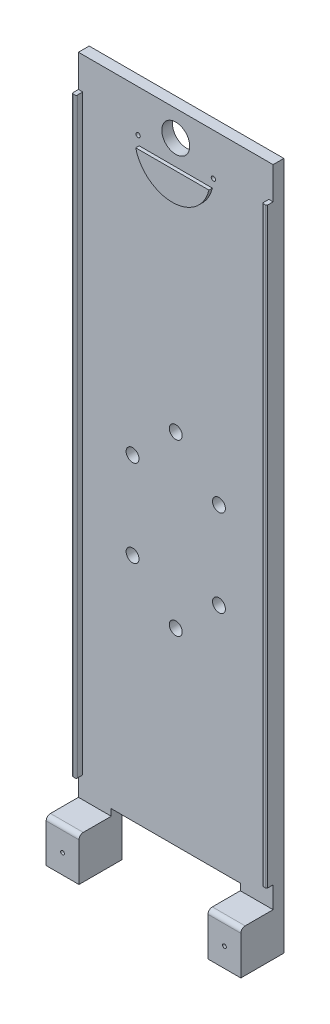
SolidWorks part; units mm, degrees
ref_plane "Front Plane" through (0, 0, 0) normal (1, 0, 0) x (0, 1, 0)
ref_plane "Top Plane" through (0, 0, 0) normal (0, 0, 1) x (0, 1, 0)
ref_plane "Right Plane" through (0, 0, 0) normal (0, 1, 0) x (-1, 0, 0)
sketch "Sketch1" plane through (0, 0, 0) normal (0, 0, 1) x (0, 1, 0)
  line L1 (-160, 45.255) -> (160, 45.255)
  line L2 (-160, 45.255) -> (-160, -45.255)
  line L3 (-160, -45.255) -> (160, -45.255)
  line L4 (160, 45.255) -> (160, -45.255)
  point P4 (-160, 0)
  point P6 (0, 45.255)
  dimension "D1" = 320
  dimension "D2" = 90.51
extrude "Chassis Base" add sketch "Sketch1" along normal blind 5
sketch "Sketch3" plane through (0, 0, 5) normal (0, 0, 1) x (1, 0, 0)
  line L0 (-45.255, 160) -> (-45.255, -160) construction
  line L1 (-45.255, 145) -> (-43.255, 145)
  line L2 (-45.255, 145) -> (-45.255, -130)
  line L3 (-45.255, -130) -> (-43.255, -130)
  line L4 (-43.255, 145) -> (-43.255, -130)
  line L5 (0, 93.4321) -> (0, -103.6661) construction
  line L6 (45.255, -130) -> (43.255, -130)
  line L7 (43.255, 145) -> (43.255, -130)
  line L8 (45.255, 145) -> (43.255, 145)
  line L9 (45.255, 145) -> (45.255, -130)
  line L10 (45.255, 160) -> (-45.255, 160) construction
  line L11 (-45.255, -160) -> (45.255, -160) construction
  dimension "D1" = 15
  dimension "D2" = 2
  dimension "D3" = 30
extrude "Lateral Guard" add sketch "Sketch3" along normal blind 3
sketch "Sketch4" plane through (0, 0, 0) normal (0, 0, -1) x (1, 0, 0)
  line L0 (0, 151.0561) -> (0, 81.1618) construction
  line L1 (-20.08, 30) -> (20.08, 30) construction
  line L3 (-45.255, 160) -> (45.255, 160) construction
  circle A0 centre (0, -29.7) radius 3
  circle A1 centre (-20.08, 30) radius 3
  circle A2 centre (20.08, 30) radius 3
  circle A3 centre (0, 49.3) radius 3
  circle A4 centre (-20.08, -10.4) radius 3
  circle A5 centre (20.08, -10.4) radius 3
  dimension "D1" = 6
  dimension "D2" = 6
  dimension "D5" = 6
  dimension "D8" = 6
  dimension "D9" = 6
  dimension "D3" = 40.16
  dimension "D4" = 59.7
  dimension "D6" = 130
  dimension "D7" = 79
  dimension "D10" = 59.7
extrude "Drive Attachment Point" cut sketch "Sketch4" against normal up to next
sketch "Sketch5" plane through (0, 0, 5) normal (0, 0, 1) x (1, 0, 0)
  line L0 (0, 137.6641) -> (0, 62.7998) construction
  line L1 (45.255, 160) -> (-45.255, 160) construction
  circle A0 centre (0, 148) radius 6.5
  circle A1 centre (-17.5, 140.5) radius 1
  circle A2 centre (17.5, 140.5) radius 1
  dimension "D1" = 13
  dimension "D3" = 2
  dimension "D2" = 35
  dimension "D4" = 12
  dimension "D5" = 7.5
extrude "Cut-Extrude2" cut sketch "Sketch5" against normal up to next
sketch "Sketch6" plane through (45.255, 0, 0) normal (1, 0, 0) x (0, 1, 0)
  line L1 (-160, 0) -> (-140, 0)
  line L2 (-160, 0) -> (-160, 20)
  line L3 (-160, 20) -> (-140, 20)
  line L4 (-140, 0) -> (-140, 20)
  dimension "D1" = 20
  dimension "D2" = 20
extrude "Boss-Extrude1" add sketch "Sketch6" against normal up to surface (90.51 mm away) up to face at (-45.255, 3.75, 4.5)
sketch "Sketch7" plane through (0, 0, 20) normal (0, 0, 1) x (1, 0, 0)
  line L0 (0, -69.6733) -> (0, -134.8619) construction
  line L2 (-30, -160) -> (30, -160)
  line L3 (-30, -160) -> (-30, -136.9264)
  line L4 (-30, -136.9264) -> (30, -136.9264)
  line L5 (30, -160) -> (30, -136.9264)
  line L6 (-30, -160) -> (30, -136.9264) construction
  line L7 (-30, -136.9264) -> (30, -160) construction
  line L8 (-45.255, -160) -> (45.255, -160) construction
  point P1 (0, -147)
  dimension "D1" = 60
extrude "Cut-Extrude3" cut sketch "Sketch7" against normal up to next
sketch "Sketch8" plane through (-45.255, 0, 0) normal (-1, 0, 0) x (0, -1, 0)
  circle A0 centre (150, 10.537) radius 5
  dimension "D1" = 10
extrude "Cut-Extrude4" [suppressed] cut sketch "Sketch8" against normal through all
fillet "Fillet1" [suppressed] radius 1
fillet "Fillet2" [suppressed] radius 1
fillet "Fillet3" radius 0.5 4 edges at (43.255, 7.5, 8) (45.255, 7.5, 8) (-43.255, 7.5, 8) (-45.255, 7.5, 8)
fillet "Fillet4" radius 2 2 edges at (-37.6275, -140, 20) (37.6275, -140, 20)
sketch "Sketch9" plane through (0, 0, 20) normal (0, 0, 1) x (1, 0, 0)
  line L0 (-37.6275, -142) -> (-37.6275, -160) construction
  line L1 (-30, -142) -> (-45.255, -142) construction
  line L2 (-45.255, -160) -> (-30, -160) construction
  line L3 (-45.255, -151) -> (-30, -151) construction
  line L4 (-45.255, -160) -> (-45.255, -142) construction
  line L5 (-30, -142) -> (-30, -160) construction
  circle A0 centre (-37.6275, -151) radius 0.875
  dimension "D1" = 1.75
extrude "Cut-Extrude5" cut sketch "Sketch9" against normal blind 5
sketch "Sketch10" plane through (0, -160, 0) normal (0, -1, 0) x (1, 0, 0)
  line L0 (-37.6275, 20) -> (-37.6275, 0) construction
  line L1 (-45.255, 20) -> (-30, 20) construction
  line L2 (-45.255, 0) -> (-30, 0) construction
  line L3 (-45.255, 10) -> (-30, 10) construction
  line L4 (-45.255, 20) -> (-45.255, 0) construction
  line L5 (-30, 0) -> (-30, 20) construction
  circle A0 centre (-37.6275, 10) radius 0.875
  dimension "D1" = 1.75
extrude "Cut-Extrude6" cut sketch "Sketch10" against normal blind 5
sketch "Sketch11" plane through (0, 0, 0) normal (0, 0, -1) x (1, 0, 0)
  line L0 (-37.6275, 160) -> (-37.6275, 137.1992) construction
  line L1 (-45.255, 160) -> (-30, 160) construction
  line L2 (-30, 148.4632) -> (-45.255, 148.4632) construction
  line L3 (-30, 160) -> (-30, 136.9264) construction
  line L4 (-45.255, -160) -> (-45.255, 160) construction
  circle A0 centre (-37.6275, 148.5996) radius 0.875
  dimension "D1" = 1.75
extrude "Cut-Extrude7" cut sketch "Sketch11" against normal blind 5
sketch "Sketch12" plane through (0, 0, 0) normal (0, 0, -1) x (1, 0, 0)
  line L0 (37.6275, 160) -> (37.6275, 137.7351) construction
  line L1 (30, 160) -> (45.255, 160) construction
  line L2 (30, 148.4632) -> (45.255, 148.4632) construction
  line L3 (30, 136.9264) -> (30, 160) construction
  line L4 (45.255, 160) -> (45.255, -160) construction
  circle A0 centre (37.6275, 148.4632) radius 0.875
  dimension "D1" = 1.75
extrude "Cut-Extrude8" cut sketch "Sketch12" against normal blind 5
sketch "Sketch13" plane through (0, -160, 0) normal (0, -1, 0) x (1, 0, 0)
  line L0 (37.6275, 20) -> (37.6275, 0) construction
  line L1 (30, 20) -> (45.255, 20) construction
  line L2 (30, 0) -> (45.255, 0) construction
  line L3 (45.255, 10) -> (30, 10) construction
  line L4 (45.255, 20) -> (45.255, 0) construction
  line L5 (30, 0) -> (30, 20) construction
  circle A0 centre (37.6275, 10) radius 0.875
  dimension "D1" = 1.75
extrude "Cut-Extrude9" cut sketch "Sketch13" against normal blind 5
sketch "Sketch14" plane through (0, 0, 20) normal (0, 0, 1) x (1, 0, 0)
  line L0 (37.6275, -160) -> (37.6275, -142) construction
  line L1 (30, -160) -> (45.255, -160) construction
  line L2 (45.255, -142) -> (30, -142) construction
  line L3 (30, -151) -> (45.255, -151) construction
  line L4 (30, -160) -> (30, -142) construction
  line L5 (45.255, -142) -> (45.255, -160) construction
  circle A0 centre (37.6275, -151) radius 0.875
  dimension "D1" = 1.75
extrude "Cut-Extrude10" cut sketch "Sketch14" against normal blind 5
sketch "Sketch15" plane through (0, 0, 5) normal (0, 0, 1) x (1, 0, 0)
  line L0 (-17.0216, 136.4361) -> (17.0216, 136.4361)
  arc A0 (-17.0216, 136.4361) -> (17.0216, 136.4361) centre (0, 140.5) ccw
extrude "Boss-Extrude2" add sketch "Sketch15" along normal blind 1.6
